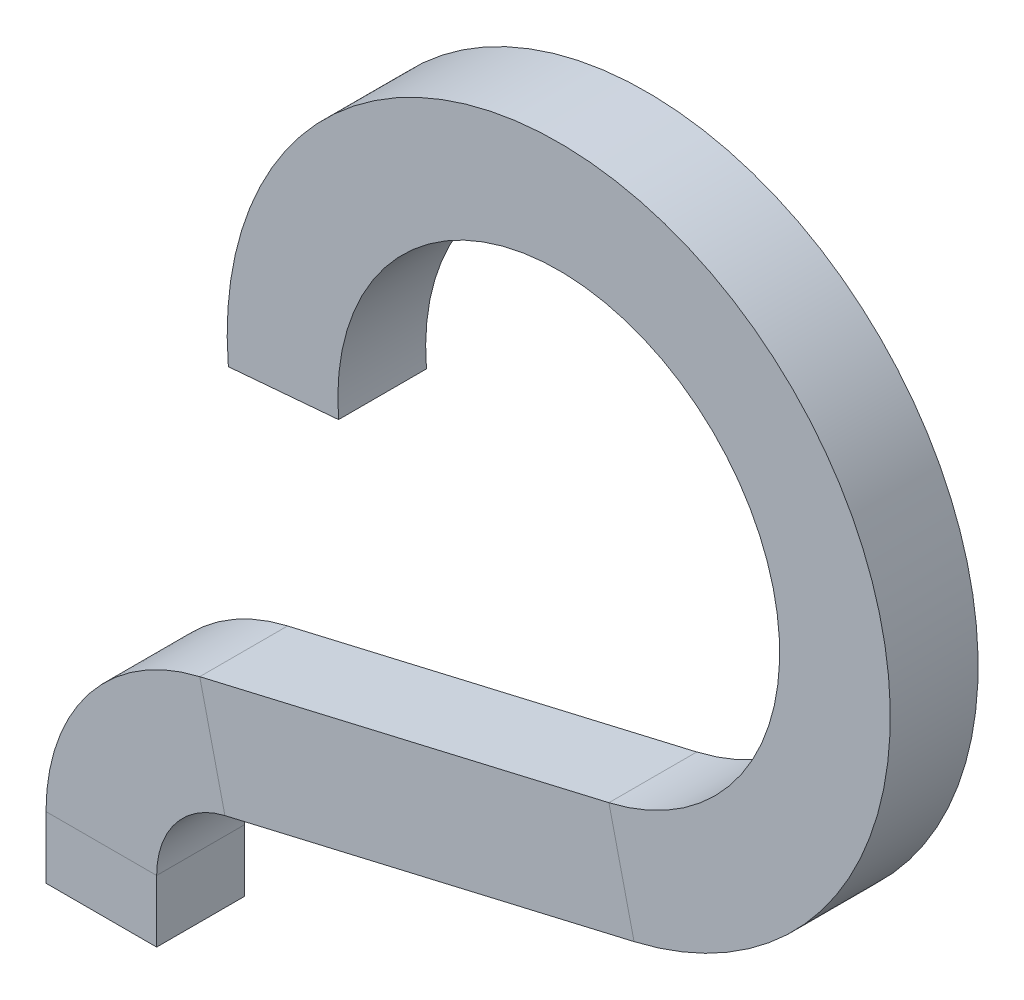
SolidWorks part; units mm, degrees
material "AISI 1020"
ref_plane "Front Plane" through (0, 0, 0) normal (0, 0, 1) x (1, 0, 0)
ref_plane "Top Plane" through (0, 0, 0) normal (0, 1, 0) x (1, 0, 0)
ref_plane "Right Plane" through (0, 0, 0) normal (1, 0, 0) x (0, 0, -1)
sketch "Sketch1" plane through (0, 0, 0) normal (0, 1, 0) x (1, 0, 0)
  circle A0 centre (0, 0) radius 15
  dimension "D1" = 30
sketch "Sketch2" plane through (0, 0, 0) normal (0, 0, 1) x (1, 0, 0)
  line L0 (0, 0) -> (0, 20.5388)
  line L1 (39.7226, 70.5904) -> (175.1259, 102.1659)
  arc A0 (0, 20.5388) -> (39.7226, 70.5904) centre (51.3944, 20.5388) cw
  arc A1 (175.1259, 102.1659) -> (67.9905, 180.0799) centre (155.2408, 187.438) ccw
ref_plane "Plane1" through (67.9905, 180.0799, 0) normal (0.084, -0.9965, 0) x (-0.9965, -0.084, 0)
sketch "Sketch3" plane through (67.9905, 180.0799, 0) normal (0.084, -0.9965, 0) x (-0.9965, -0.084, 0)
  line L1 (-14.4458, 14.1552) -> (22.169, 14.1552)
  line L2 (-14.4458, 14.1552) -> (-14.4458, -14.9102)
  line L3 (-14.4458, -14.9102) -> (22.169, -14.9102)
  line L4 (22.169, 14.1552) -> (22.169, -14.9102)
sweep "Sweep2" add profiles "Sketch3" path "Sketch2"
